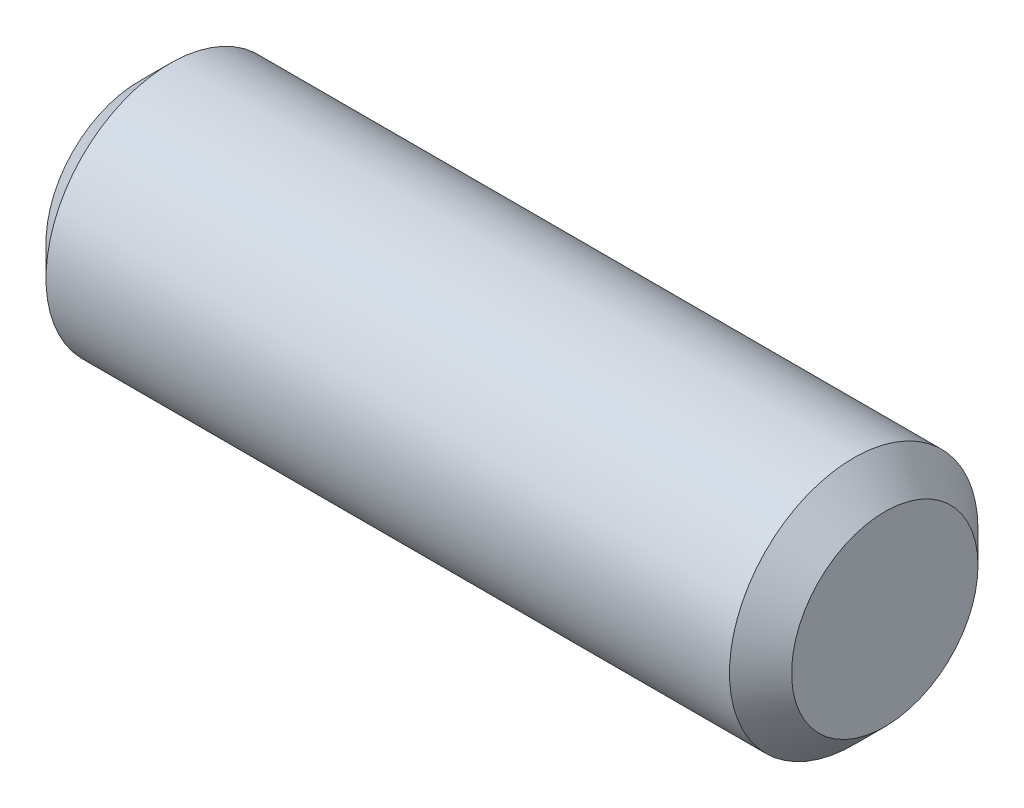
SolidWorks part; units mm, degrees
ref_plane "前基準面" through (0, 0, 0) normal (0, 0, 1) x (1, 0, 0)
ref_plane "上基準面" through (0, 0, 0) normal (0, 1, 0) x (1, 0, 0)
ref_plane "右基準面" through (0, 0, 0) normal (1, 0, 0) x (0, 0, -1)
ref_plane "平面1"
sketch "草圖1" plane through (0, 0, 0) normal (1, 0, 0) x (0, 1, 0)
  circle A0 centre (0, 0) radius 4
  dimension "D1" = 8
extrude "擠出1" add sketch "草圖1" along normal blind 12 and the other way blind 12
chamfer "倒角1" distance 1 distance2 1 2 edges at (12, 0, -4) (-12, 0, -4)
